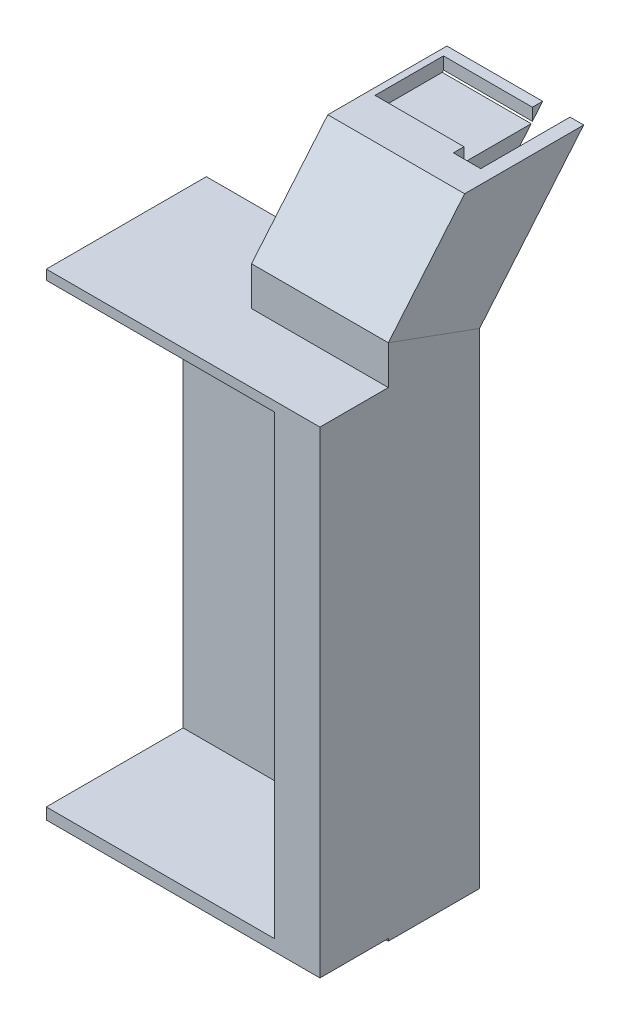
SolidWorks part; units mm, degrees
ref_plane "前视基准面" through (0, 0, 0) normal (0, 0, 1) x (1, 0, 0)
ref_plane "上视基准面" through (0, 0, 0) normal (0, 1, 0) x (1, 0, 0)
ref_plane "右视基准面" through (0, 0, 0) normal (1, 0, 0) x (0, 0, -1)
sketch "草图1" plane through (0, 0, 0) normal (0, 1, 0) x (1, 0, 0)
  line L0 (-17.5699, 4.6329) -> (-17.5699, -15.3671)
  line L1 (-17.5699, -15.3671) -> (12.4301, -15.3671)
  line L2 (12.4301, -15.3671) -> (12.4301, 4.6329)
  line L3 (12.4301, 4.6329) -> (-17.5699, 4.6329)
  line L4 (-17.5699, 4.6329) -> (12.4301, -15.3671) construction
  line L5 (-17.5699, -15.3671) -> (12.4301, 4.6329) construction
  line L6 (-2.5699, 4.6329) -> (-2.5699, -15.3671) construction
  line L9 (-2.5699, 4.6329) -> (0, 4.6329)
  point P3 (-2.5699, -5.3671)
  dimension "D1" = 30
  dimension "D2" = 20
ref_plane "基准面1" through (-2.57, 0, 0) normal (1, 0, 0) x (0, 0, -1)
sketch "草图2" plane through (-2.57, 0, 0) normal (1, 0, 0) x (0, 0, -1)
  line L0 (-5.3671, 0) -> (-5.3671, 110)
  line L1 (-5.3671, 110) -> (19.8059, 140)
  dimension "D1" = 110
  dimension "D2" = 30
  dimension "D3" = 220
sweep "扫描1" add profiles "草图1" path "草图2"
sketch "草图3" plane through (0, 0, 0) normal (0, -1, 0) x (1, 0, 0)
  line L0 (-17.5699, -4.6329) -> (12.4301, -4.6329)
  line L1 (12.4301, -4.6329) -> (12.4301, 5.3671)
  line L2 (12.4301, 15.3671) -> (12.4301, -4.6329) construction
  line L3 (12.4301, 5.3671) -> (-17.5699, 5.3671)
  line L4 (-17.5699, -4.6329) -> (-17.5699, 15.3671) construction
  line L5 (-17.5699, 5.3671) -> (-17.5699, -4.6329)
ref_plane "基准面2" through (6.4301, 0, 0) normal (1, 0, 0) x (0, 0, -1)
sketch "草图16" plane through (0, 91.9079, -77.1198) normal (0, 0.766, -0.6428) x (1, 0, 0)
  line L0 (3.4301, -64.8181) -> (9.4301, -64.8181)
  line L1 (12.4301, -64.8181) -> (-17.5699, -64.8181) construction
  line L2 (9.4301, -64.8181) -> (9.4301, -79.8181)
  line L3 (9.4301, -79.8181) -> (3.4301, -79.8181)
  line L4 (3.4301, -79.8181) -> (3.4301, -64.8181)
  line L5 (12.4301, -84.8181) -> (12.4301, -64.8181) construction
  line L6 (3.4301, -64.8181) -> (9.4301, -79.8181) construction
  line L7 (9.4301, -64.8181) -> (3.4301, -79.8181) construction
  point P8 (6.4301, -72.3181)
  dimension "D1" = 15
  dimension "D2" = 6
  dimension "D3" = 3
sketch "草图19" plane through (6.4301, 0, 0) normal (1, 0, 0) x (0, 0, -1)
  line L0 (21.721, 138.393) -> (-2.8671, 109.0901)
  line L1 (4.6329, 106.3603) -> (-15.3671, 113.6397) construction
  line L2 (-2.8671, 109.0901) -> (-2.8671, 0)
  line L3 (27.4663, 133.5721) -> (15.9756, 143.2139) construction
  line L4 (-15.3671, 0) -> (4.6329, 0) construction
sweep "切除-扫描2" cut profiles "草图16" path "草图19"
sketch "草图20" plane through (0, 0, 15.3671) normal (0, 0, 1) x (1, 0, 0)
  line L3 (2.4301, 3) -> (2.4301, 103)
  line L6 (2.4301, 103) -> (-41.5792, 103)
  line L7 (-41.5792, 103) -> (-41.5792, 3)
  line L8 (-41.5792, 3) -> (2.4301, 3)
  dimension "D2" = 100
extrude "arduino安装槽" cut sketch "草图20" against normal blind 15
sketch "草图36" plane through (0, 0, 0) normal (0, -1, 0) x (1, 0, 0)
  line L0 (-17.5699, 15.3671) -> (-2.5699, 15.3671)
  line L1 (-17.5699, 15.3671) -> (12.4301, 15.3671) construction
  line L2 (-2.5699, 15.3671) -> (-2.5699, 5.3671)
  line L3 (12.4301, 5.3671) -> (-17.5699, 5.3671) construction
  line L4 (-2.5699, 5.3671) -> (-17.5699, 5.3671)
  line L5 (-17.5699, 5.3671) -> (-17.5699, 15.3671)
extrude "凸台-拉伸1" add sketch "草图36" along normal blind 10
sketch "草图37" plane through (-17.5699, 0, 0) normal (-1, 0, 0) x (0, 0, 1)
  line L0 (5.3671, -10) -> (5.3671, -5)
  line L1 (5.3671, -10) -> (5.3671, 0) construction
  line L2 (5.3671, -10) -> (10.3671, -10)
  line L3 (15.3671, -10) -> (5.3671, -10) construction
  arc A0 (5.3671, -5) -> (10.3671, -10) centre (10.3671, -5) ccw
extrude "切除-拉伸25" cut sketch "草图37" against normal blind 15
sketch "草图40" plane through (-17.5699, 0, 0) normal (-1, 0, 0) x (0, 0, 1)
  line L0 (-27.4663, 133.5721) -> (-1.3582, 133.5721)
  line L1 (15.3671, 113.6397) -> (-12.1454, 146.4279) construction
  line L2 (-27.4663, 133.5721) -> (-12.1454, 146.4279)
  line L3 (-12.1454, 146.4279) -> (-1.3582, 133.5721)
extrude "切除-拉伸28" cut sketch "草图40" against normal blind 30
sketch "草图41" plane through (0, 133.5721, 0) normal (0, 1, 0) x (1, 0, 0)
  line L0 (3.4301, 10.2163) -> (-16.0736, 10.2163)
  line L1 (3.4301, 7.8852) -> (3.4301, 27.4663) construction
  line L2 (-16.0736, 10.2163) -> (-16.0736, 25.2163)
  line L3 (-16.0736, 25.2163) -> (3.4301, 25.2163)
  line L4 (3.4301, 25.2163) -> (3.4301, 10.2163)
  line L5 (3.4301, 27.4663) -> (-17.5699, 27.4663) construction
  dimension "D1" = 15
  dimension "D2" = 2.25
extrude "切除-拉伸29" cut sketch "草图41" against normal blind 3
sketch "草图42" plane through (-17.5699, 0, 0) normal (-1, 0, 0) x (0, 0, 1)
  line L0 (-4.7308, 105.1282) -> (-4.6329, 0.5138)
  line L1 (-4.6329, 0) -> (-4.6329, 106.3603) construction
  line L2 (-4.6329, 0.5138) -> (15.3671, 0.5138)
  line L3 (15.3671, -10) -> (15.3671, 3) construction
  line L4 (15.3671, 0.5138) -> (15.3671, 105.1282)
  line L5 (15.3671, 103) -> (15.3671, 113.6397) construction
  line L6 (15.3671, 3) -> (15.3671, 103) construction
  line L7 (15.3671, 105.1282) -> (-4.7308, 105.1282)
extrude "凸台-拉伸2" add sketch "草图42" along normal blind 30
sketch "草图46" plane through (0, 0, 15.3671) normal (0, 0, 1) x (1, 0, 0)
  line L1 (-17.5699, 103) -> (-17.5699, 3)
  line L2 (-17.5699, 3) -> (-47.5699, 3)
  line L3 (-47.5699, 0.5138) -> (-47.5699, 105.1282) construction
  line L4 (-47.5699, 3) -> (-47.5699, 103)
  line L5 (-47.5699, 103) -> (-17.5699, 103)
extrude "切除-拉伸31" cut sketch "草图46" against normal blind 15
sketch "草图47" plane through (0, 0, 15.3671) normal (0, 0, 1) x (1, 0, 0)
  line L0 (-47.5699, 105.1282) -> (-47.5699, 103)
  line L1 (-47.5699, 103) -> (2.4301, 103)
  line L2 (2.4301, 103) -> (2.4301, 3)
  line L3 (2.4301, 3) -> (-47.5699, 3)
  line L4 (-47.5699, 3) -> (-47.5699, 0.5138)
  line L5 (-47.5699, 0.5138) -> (12.4301, 0.5138)
  line L6 (12.4301, 0) -> (12.4301, 113.6397) construction
  line L7 (12.4301, 0.5138) -> (12.4301, 105.1282)
  line L8 (12.4301, 105.1282) -> (-47.5699, 105.1282)
extrude "凸台-拉伸3" add sketch "草图47" along normal blind 15
sketch "草图48" plane through (2.4301, 0, 0) normal (-1, 0, 0) x (0, 0, 1)
  line L0 (2.8817, 103) -> (8.8817, 103)
  line L1 (0.3671, 103) -> (30.3671, 103) construction
  line L2 (8.8817, 103) -> (8.8817, 3)
  line L3 (0.3671, 3) -> (30.3671, 3) construction
  line L4 (8.8817, 3) -> (2.8817, 3)
  line L5 (2.8817, 3) -> (2.8817, 103)
  dimension "D1" = 6
extrude "切除-拉伸32" cut sketch "草图48" against normal blind 5
sketch "草图49" plane through (-17.5699, 0, 0) normal (-1, 0, 0) x (0, 0, 1)
  circle A0 centre (10.3671, -5) radius 1.5
  dimension "D1" = 3
extrude "切除-拉伸33" cut sketch "草图49" against normal blind 15
